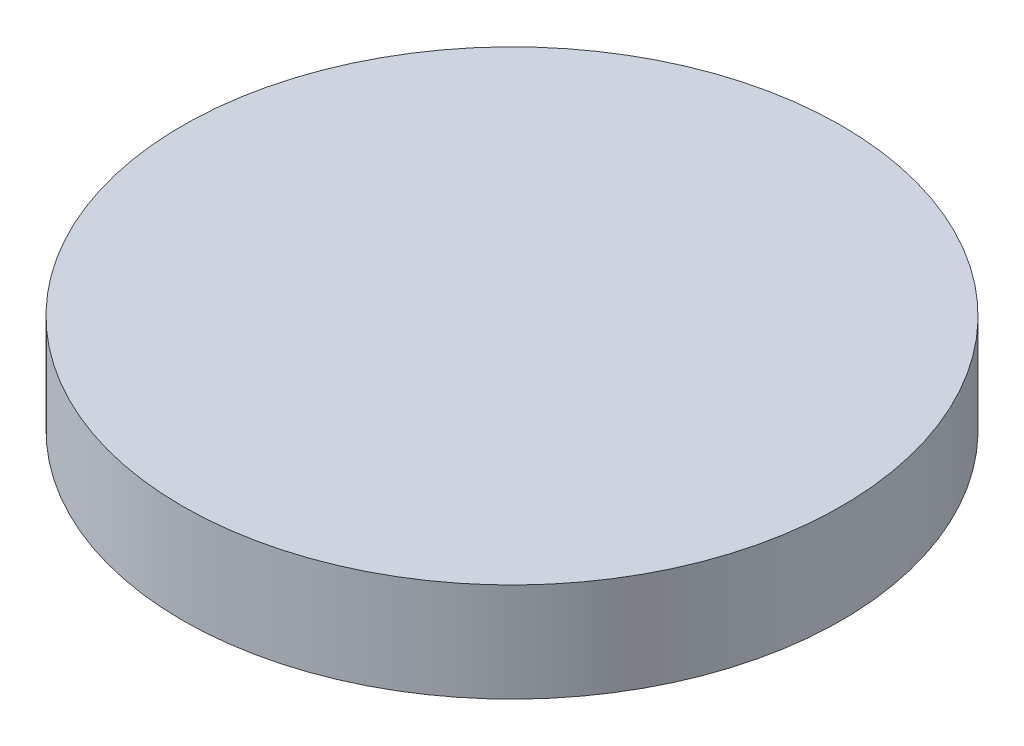
SolidWorks part; units mm, degrees
ref_plane "Front Plane" through (0, 0, 0) normal (0, 0, 1) x (1, 0, 0)
ref_plane "Top Plane" through (0, 0, 0) normal (0, 1, 0) x (1, 0, 0)
ref_plane "Right Plane" through (0, 0, 0) normal (1, 0, 0) x (0, 0, -1)
sketch "Sketch1" plane through (0, 0, 0) normal (0, 1, 0) x (1, 0, 0)
  circle A0 centre (0, 0) radius 25.4
extrude "Boss-Extrude2" add sketch "Sketch1" along normal blind 7.62 contours A0
sketch "Sketch4" plane through (0, 0, 0) normal (0, 1, 0) x (1, 0, 0)
  circle A0 centre (0, 0) radius 17.78 construction
  circle A1 centre (0, 17.78) radius 4.826
extrude "Cut-Extrude2" cut sketch "Sketch4" along normal blind 6.096
pattern_circular "CirPattern1" count 6 over 360 about axis through (0, 0, 0) along (0, 1, 0) of "Cut-Extrude2"
sketch "Sketch5" plane through (0, 0, 0) normal (0, 1, 0) x (1, 0, 0)
  circle A0 centre (0, 0) radius 4.826
sketch "Sketch6" plane through (0, 7.62, 0) normal (0, 1, 0) x (1, 0, 0)
  circle A0 centre (0, 0) radius 12.7
extrude "Boss-Extrude4" [suppressed] add sketch "Sketch6" along normal blind 41.91 draft 7
extrude "Cut-Extrude6" cut sketch "Sketch5" along normal blind 6.096
scale "Scale1" bodies to scale 110 scale about centroid uniform scaling yes scale factor 0.5
sketch "Sketch7" plane through (0, 5.8115, 0) normal (0, 1, 0) x (1, 0, 0)
  circle A0 centre (0, 0) radius 3.175
